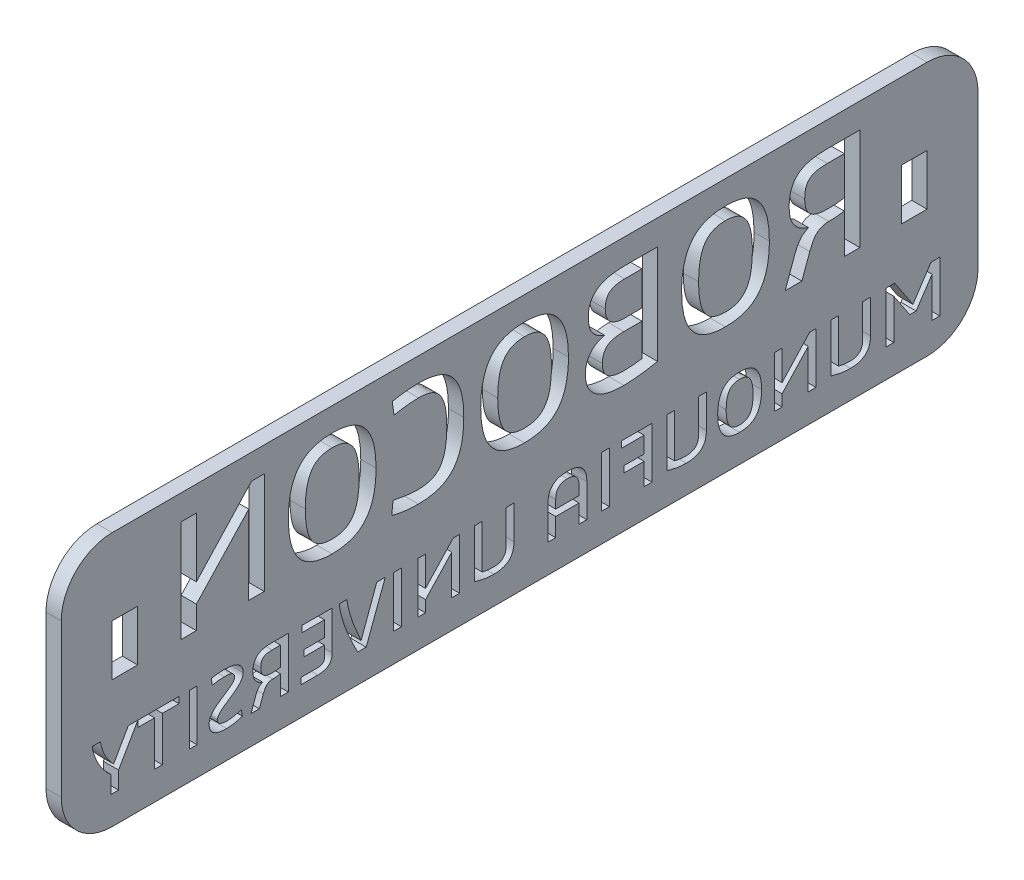
SolidWorks part; units mm, degrees
ref_plane "Front Plane" through (0, 0, 0) normal (0, 0, 1) x (1, 0, 0)
ref_plane "Top Plane" through (0, 0, 0) normal (0, 1, 0) x (1, 0, 0)
ref_plane "Right Plane" through (0, 0, 0) normal (1, 0, 0) x (0, 0, -1)
sketch "Sketch1" plane through (0, 0, 0) normal (1, 0, 0) x (0, 0, -1)
  line L0 (0, -7.5455) -> (0, 13.1234) construction
  line L1 (-90, -25) -> (90, -25)
  line L2 (-90, -25) -> (-90, 25)
  line L3 (-90, 25) -> (90, 25)
  line L4 (90, -25) -> (90, 25)
  line L5 (-90, -25) -> (90, 25) construction
  line L6 (-90, 25) -> (90, -25) construction
  line L7 (-80, 0) -> (-75, 0)
  line L8 (-80, 0) -> (-80, 10)
  line L9 (-80, 10) -> (-75, 10)
  line L10 (-75, 0) -> (-75, 10)
  line L11 (-80, 0) -> (-75, 10) construction
  line L12 (-80, 10) -> (-75, 0) construction
  line L13 (80, 0) -> (75, 0)
  line L14 (80, 0) -> (80, 10)
  line L15 (80, 10) -> (75, 10)
  line L16 (75, 0) -> (75, 10)
  point P0 (0, 0)
  point P6 (-77.5, 5)
  point P17 (0, 0)
  dimension "D1" = 180
  dimension "D2" = 50
  dimension "D3" = 150
  dimension "D4" = 10
  dimension "D5" = 5
extrude "Boss-Extrude1" add sketch "Sketch1" along normal blind 3
fillet "Fillet1" radius 10 4 edges at (1.5, -25, -90) (1.5, -25, 90) (1.5, 25, 90) (1.5, 25, -90)
sketch "Sketch3" plane through (0, 0, 0) normal (-1, 0, 0) x (0, 0, 1)
  line L0 (-75, 0.0687) -> (75, 0.0687) construction
  line L1 (-75, 10) -> (-75, 0) construction
  line L2 (75, 0) -> (75, 10) construction
  line L3 (-90, -19.4037) -> (90, -19.4037) construction
  text T0 "ROBOCON" font "3ds" height 20
  text T1 "MUNOUFIA UNIVERSITY" font "3ds" height 10
  point P8 (0, -19.4037)
  point P9 (0, 0.0687)
extrude "Cut-Extrude2" cut sketch "Sketch3" against normal through all
